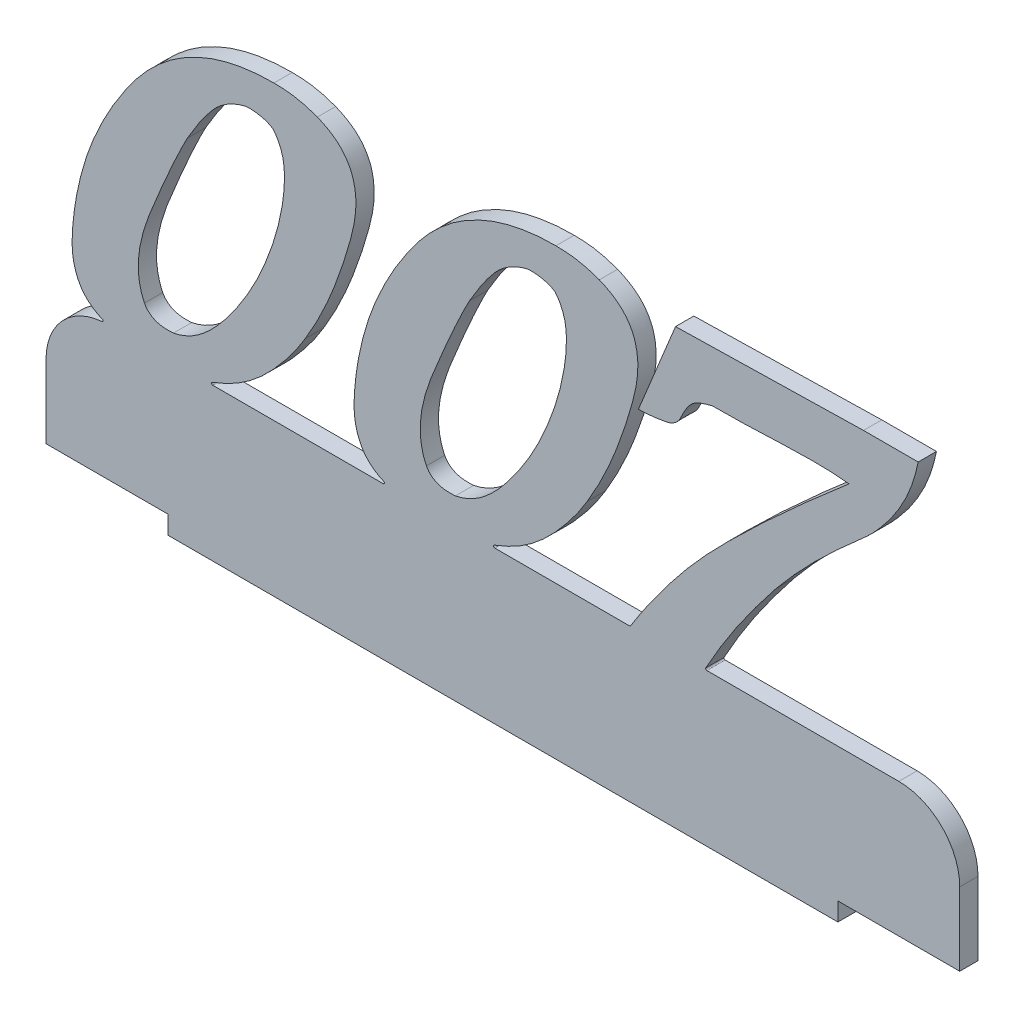
SolidWorks part; units mm, degrees
ref_plane "Front Plane" through (0, 0, 0) normal (0, 0, 1) x (1, 0, 0)
ref_plane "Top Plane" through (0, 0, 0) normal (0, 1, 0) x (1, 0, 0)
ref_plane "Right Plane" through (0, 0, 0) normal (1, 0, 0) x (0, 0, -1)
sketch "Sketch1" plane through (0, 0, 0) normal (0, 0, 1) x (1, 0, 0)
  line L0 (0, 20) -> (150, 20) construction
  line L1 (108.157, 22) -> (150, 22)
  line L2 (0, 22) -> (0, 0)
  line L3 (0, 0) -> (20, 0)
  line L4 (150, 22) -> (150, 0)
  line L5 (0, 22) -> (10.2732, 22)
  line L6 (97.2666, 53.5536) -> (103.3456, 68.3307)
  line L7 (103.3456, 68.3307) -> (134.2095, 68.9953)
  line L8 (134.2095, 68.9953) -> (143.1814, 68.9953)
  line L9 (26.2041, 22) -> (56.5594, 22)
  line L10 (72.4903, 22) -> (95.909, 22)
  line L11 (130, 0) -> (150, 0)
  line L13 (20, 0) -> (20, -3)
  line L14 (20, -3) -> (130, -3)
  line L15 (130, 0) -> (130, -3)
  spline S0 degree 3 poles (37.2783, 63.3855) (36.6771, 63.795) (35.2118, 64.3011) (33.674, 64.4284) (32.8608, 64.3823) knots 0 0 0 0 0.469699 1 1 1 1
  spline S1 degree 3 poles (32.8608, 64.3823) (31.7161, 64.1416) (30.0981, 63.4641) (28.2097, 62.0865) (25.9018, 59.5085) (24.3681, 57.0569) (23.2244, 55.0782) knots 0 0 0 0 0.25259 0.375811 0.50377 1 1 1 1
  spline S2 degree 3 poles (23.2244, 55.0782) (22.7681, 54.2801) (22.1699, 52.9636) (21.2784, 51.1445) (20.5649, 49.563) (19.8005, 47.8437) (19, 45.977) (18.1434, 43.9808) (17.2714, 41.8925) (16.4784, 39.7943) (15.8467, 37.7669) (15.4059, 35.8598) (15.163, 34.0668) (15.1157, 32.3875) (15.3174, 30.3618) (15.7369, 28.9382) (16.1681, 28.0844) knots 0 0 0 0 0.095871 0.150957 0.21155 0.277044 0.347448 0.42366 0.503899 0.583776 0.657815 0.725493 0.787949 0.846481 0.90051 1 1 1 1
  spline S3 degree 3 poles (16.1681, 28.0844) (16.5265, 27.3414) (18.026, 26.1341) (19.9389, 26.1176) (20.9179, 26.1884) knots 0 0 0 0 0.446154 1 1 1 1
  spline S4 degree 3 poles (20.9179, 26.1884) (22.3754, 26.4628) (24.532, 27.4812) (27.0643, 29.649) (29.0148, 31.8062) (30.8816, 34.2917) (32.6431, 36.9657) (34.2336, 39.7922) (35.6281, 42.7484) (36.8262, 45.7654) (37.8178, 48.7775) (38.5365, 51.766) (39.041, 54.6566) (39.2106, 57.3583) (39.0087, 60.3889) (38.1339, 62.3774) (37.2783, 63.3855) knots 0 0 0 0 0.099523 0.157976 0.224341 0.295662 0.367825 0.440561 0.514606 0.588508 0.65979 0.72866 0.796042 0.857776 0.911265 1 1 1 1
  spline S5 degree 3 poles (10.2732, 22) (10.2249, 22.0147) (9.6548, 22.1899) (8.6074, 22.5588) (7.301, 23.4087) (6.191, 24.4277) (5.3611, 25.705) (4.7557, 27.1765) (4.202, 29.5414) (4.2717, 31.4611) (4.362, 32.7756) knots 0.495745 0.495745 0.495745 0.495745 0.501388 0.5623 0.61932 0.674488 0.729675 0.788153 0.851799 1 1 1 1
  spline S6 degree 3 poles (4.362, 32.7756) (4.5289, 35.0037) (5.0181, 38.3293) (6.1475, 42.6661) (7.2103, 45.8754) (8.565, 49.0088) (10.103, 52.1146) (11.9107, 55.1578) (13.9178, 58.1249) (16.1153, 60.9142) (18.5896, 63.3331) (21.2318, 65.4207) (24.1121, 67.0681) (27.1476, 68.4159) (31.57, 69.6382) (35.0487, 70.023) (37.4152, 69.9922) knots 0 0 0 0 0.122246 0.183381 0.245051 0.307032 0.370011 0.434579 0.500535 0.565958 0.62848 0.689454 0.749684 0.809559 0.870725 1 1 1 1
  spline S7 degree 3 poles (37.4152, 69.9922) (38.6754, 69.9817) (41.1182, 69.8382) (43.4584, 69.1284) (44.5496, 68.7217) knots 0 0 0 0 0.519885 1 1 1 1
  spline S8 degree 3 poles (44.5496, 68.7217) (45.8172, 68.2064) (47.6122, 67.213) (49.3516, 65.2301) (50.2611, 63.5566) (50.7764, 61.6517) (50.9417, 59.5347) (50.7486, 57.2039) (49.9992, 53.8645) (48.7206, 49.6981) (46.4195, 43.3945) (44.2225, 38.9682) (42.5559, 36.2158) knots 0 0 0 0 0.111906 0.162582 0.212593 0.265416 0.321766 0.384451 0.454781 0.599581 0.738515 1 1 1 1
  spline S9 degree 3 poles (42.5559, 36.2158) (41.4644, 34.3586) (39.5941, 31.7881) (36.8448, 28.6651) (34.6761, 26.5959) (32.2936, 24.7882) (29.6139, 23.2924) (27.5333, 22.4466) (26.3646, 22.0526) (26.2041, 22) knots 0 0 0 0 0.25786 0.380114 0.498337 0.616577 0.737567 0.865048 0.88527 0.88527 0.88527 0.88527
  spline S10 degree 3 poles (83.5645, 63.3855) (82.9632, 63.795) (81.498, 64.3011) (79.9602, 64.4284) (79.147, 64.3823) knots 0 0 0 0 0.469699 1 1 1 1
  spline S11 degree 3 poles (79.147, 64.3823) (78.0023, 64.1416) (76.3842, 63.4641) (74.4959, 62.0865) (72.188, 59.5085) (70.6543, 57.0569) (69.5106, 55.0782) knots 0 0 0 0 0.25259 0.375811 0.50377 1 1 1 1
  spline S12 degree 3 poles (69.5106, 55.0782) (69.0543, 54.2801) (68.4561, 52.9636) (67.5645, 51.1445) (66.8511, 49.563) (66.0867, 47.8437) (65.2862, 45.977) (64.4296, 43.9808) (63.5575, 41.8925) (62.7646, 39.7943) (62.1329, 37.7669) (61.6921, 35.8598) (61.4492, 34.0668) (61.4019, 32.3875) (61.6036, 30.3618) (62.0231, 28.9382) (62.4543, 28.0844) knots 0 0 0 0 0.095871 0.150957 0.21155 0.277044 0.347448 0.42366 0.503899 0.583776 0.657815 0.725493 0.787949 0.846481 0.90051 1 1 1 1
  spline S13 degree 3 poles (62.4543, 28.0844) (62.8127, 27.3414) (64.3122, 26.1341) (66.2251, 26.1176) (67.2041, 26.1884) knots 0 0 0 0 0.446154 1 1 1 1
  spline S14 degree 3 poles (67.2041, 26.1884) (68.6616, 26.4628) (70.8182, 27.4812) (73.3505, 29.649) (75.3009, 31.8062) (77.1677, 34.2917) (78.9293, 36.9657) (80.5197, 39.7922) (81.9142, 42.7484) (83.1124, 45.7654) (84.1039, 48.7775) (84.8226, 51.766) (85.3272, 54.6566) (85.4968, 57.3583) (85.2949, 60.3889) (84.4201, 62.3774) (83.5645, 63.3855) knots 0 0 0 0 0.099523 0.157976 0.224341 0.295662 0.367825 0.440561 0.514606 0.588508 0.65979 0.72866 0.796042 0.857776 0.911265 1 1 1 1
  spline S15 degree 3 poles (56.5594, 22) (56.511, 22.0147) (55.941, 22.1899) (54.8935, 22.5588) (53.5871, 23.4087) (52.4772, 24.4277) (51.6473, 25.705) (51.0418, 27.1765) (50.4882, 29.5414) (50.5578, 31.4611) (50.6482, 32.7756) knots 0.495745 0.495745 0.495745 0.495745 0.501388 0.5623 0.61932 0.674488 0.729675 0.788153 0.851799 1 1 1 1
  spline S16 degree 3 poles (50.6482, 32.7756) (50.8151, 35.0037) (51.3043, 38.3293) (52.4337, 42.6661) (53.4965, 45.8754) (54.8511, 49.0088) (56.3891, 52.1146) (58.1969, 55.1578) (60.2039, 58.1249) (62.4015, 60.9142) (64.8757, 63.3331) (67.518, 65.4207) (70.3982, 67.0681) (73.4337, 68.4159) (77.8561, 69.6382) (81.3348, 70.023) (83.7013, 69.9922) knots 0 0 0 0 0.122246 0.183381 0.245051 0.307032 0.370011 0.434579 0.500535 0.565958 0.62848 0.689454 0.749684 0.809559 0.870725 1 1 1 1
  spline S17 degree 3 poles (83.7013, 69.9922) (84.9616, 69.9817) (87.4044, 69.8382) (89.7446, 69.1284) (90.8358, 68.7217) knots 0 0 0 0 0.519885 1 1 1 1
  spline S18 degree 3 poles (90.8358, 68.7217) (92.1034, 68.2064) (93.8984, 67.213) (95.6377, 65.2301) (96.5472, 63.5566) (97.0625, 61.6517) (97.2278, 59.5347) (97.0347, 57.2039) (96.2853, 53.8645) (95.0068, 49.6981) (92.7056, 43.3945) (90.5087, 38.9682) (88.8421, 36.2158) knots 0 0 0 0 0.111906 0.162582 0.212593 0.265416 0.321766 0.384451 0.454781 0.599581 0.738515 1 1 1 1
  spline S19 degree 3 poles (88.8421, 36.2158) (87.7506, 34.3586) (85.8803, 31.7881) (83.1309, 28.6651) (80.9622, 26.5959) (78.5798, 24.7882) (75.9001, 23.2924) (73.8194, 22.4466) (72.6507, 22.0526) (72.4903, 22) knots 0 0 0 0 0.25786 0.380114 0.498337 0.616577 0.737567 0.865048 0.88527 0.88527 0.88527 0.88527
  spline S20 degree 3 poles (143.1814, 68.9953) (142.8722, 67.4945) (142.2594, 65.2622) (141.0015, 62.4454) (139.8597, 60.4116) (138.5449, 58.4343) (137.0059, 56.5513) (135.313, 54.6905) (132.7498, 52.4179) (129.5687, 49.6331) (124.9502, 45.155) (121.7662, 41.6808) (119.8233, 39.3041) knots 0 0 0 0 0.119749 0.17988 0.240465 0.301707 0.365036 0.430202 0.497898 0.632302 0.760396 1 1 1 1
  spline S21 degree 3 poles (119.8233, 39.3041) (117.5431, 36.4393) (114.2887, 32.1108) (110.5449, 26.2335) (108.9017, 23.3671) (108.157, 22) knots 0 0 0 0 0.515557 0.761334 0.98047 0.98047 0.98047 0.98047
  spline S22 degree 3 poles (95.909, 22) (96.9957, 23.7545) (99.3446, 27.3112) (103.2263, 32.4975) (107.5166, 37.5684) (116.819, 47.0843) (125.1177, 54.4544) (131.8444, 60.2189) knots 0.008091 0.008091 0.008091 0.008091 0.124628 0.248721 0.37378 0.49949 1 1 1 1
  spline S23 degree 3 poles (131.8444, 60.2189) (128.1108, 60.6) (120.6214, 60.4307) (113.1495, 60.0399) (109.405, 60.0821) knots 0 0 0 0 0.500072 1 1 1 1
  spline S24 degree 3 poles (109.405, 60.0821) (108.7287, 59.905) (107.5319, 59.6166) (106.4446, 59.0304) (106.043, 58.6943) knots 0 0 0 0 0.573608 1 1 1 1
  spline S25 degree 3 poles (106.043, 58.6943) (105.243, 57.9156) (104.6228, 56.7058) (103.9184, 55.2422) (103.1566, 54.473) (102.4093, 54.1422) (101.8796, 54.0227) knots 0 0 0 0 0.506425 0.630848 0.748368 1 1 1 1
  spline S26 degree 3 poles (101.8796, 54.0227) (100.9408, 53.8415) (99.4077, 53.632) (97.861, 53.4988) (97.2666, 53.5536) knots 0 0 0 0 0.616484 1 1 1 1
  dimension "D1" = 150
  dimension "D2" = 3
  dimension "D3" = 20
  dimension "D4" = 20
  dimension "D5" = 20
  dimension "D6" = 22
extrude "Boss-Extrude1" add sketch "Sketch1" along normal blind 3
fillet "Fillet1" radius 10 2 edges at (0, 22, 1.5) (150, 22, 1.5)
fillet "Fillet2" radius 0.2 6 edges at (95.909, 22, 1.5) (108.157, 22, 1.5) (72.4903, 22, 1.5) (56.5594, 22, 1.5) (26.2041, 22, 1.5) (10.2732, 22, 1.5)
